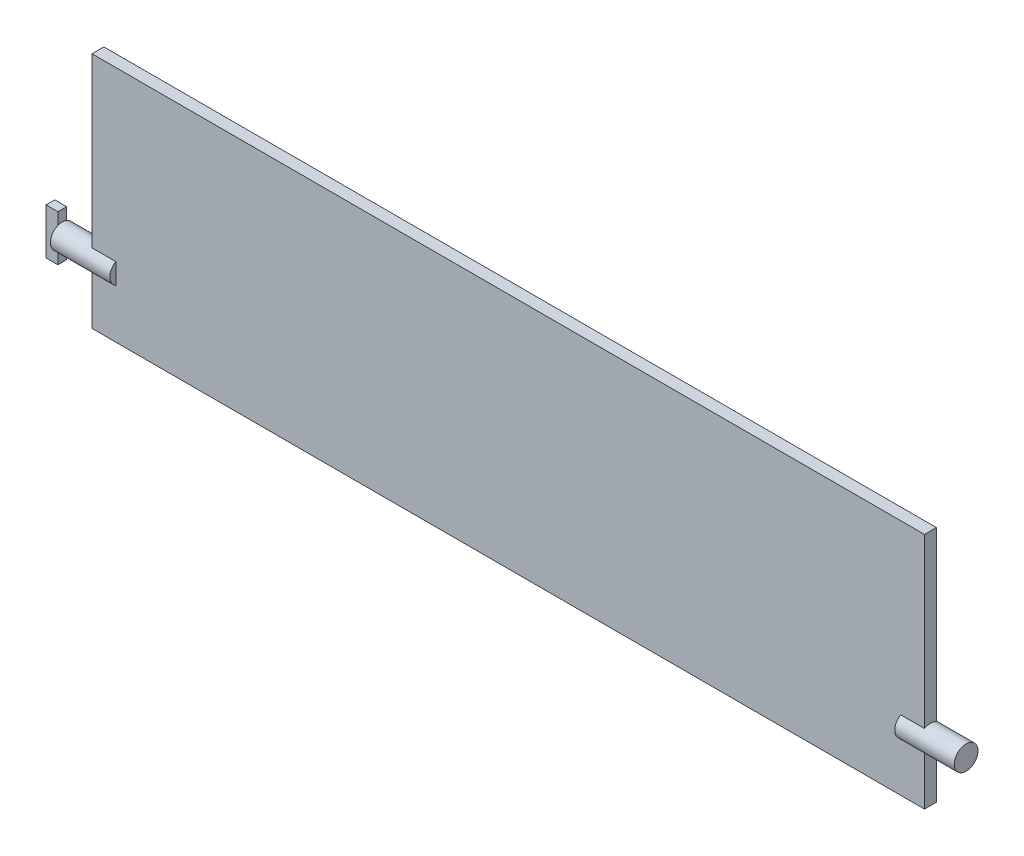
SolidWorks part; units mm, degrees
ref_plane "Front Plane" through (0, 0, 0) normal (0, 0, 1) x (1, 0, 0)
ref_plane "Top Plane" through (0, 0, 0) normal (0, 1, 0) x (1, 0, 0)
ref_plane "Right Plane" through (0, 0, 0) normal (1, 0, 0) x (0, 0, -1)
sketch "Sketch1" plane through (0, 0, 0) normal (0, 0, 1) x (1, 0, 0)
  line L1 (-175, -25) -> (175, -25)
  line L2 (-175, -25) -> (-175, 25)
  line L3 (-175, 25) -> (175, 25)
  line L4 (175, -25) -> (175, 25)
  line L5 (-175, -25) -> (175, 25) construction
  line L6 (-175, 25) -> (175, -25) construction
  point P0 (0, 0)
  dimension "D1" = 50
  dimension "D2" = 350
extrude "Boss-Extrude1" add sketch "Sketch1" along normal blind 5
sketch "Sketch2" plane through (-175, 0, 0) normal (-1, 0, 0) x (0, 0, 1)
  circle A0 centre (2.5, 0) radius 5
  dimension "D1" = 10
extrude "Boss-Extrude2" add sketch "Sketch2" along normal blind 15 and the other way blind 10
mirror "Mirror1" about plane through (0, 0, 0) normal (1, 0, 0) of "Boss-Extrude2"
sketch "Sketch4" plane through (0, 25, 0) normal (0, 1, 0) x (1, 0, 0)
  line L6 (-175, 0) -> (-175, -5)
  line L8 (-175, -5) -> (175, -5)
  line L9 (175, -5) -> (175, 0)
  line L11 (175, 0) -> (-175, 0)
  line L12 (-175, 0) -> (-175, -5)
  line L14 (-175, -5) -> (175, -5)
  line L15 (175, -5) -> (175, 0)
  line L17 (175, 0) -> (-175, 0)
  dimension "D1" = 0
extrude "Boss-Extrude4" add sketch "Sketch4" along normal blind 50
sketch "Sketch5" plane through (-190, 0, 0) normal (-1, 0, 0) x (0, 0, 1)
  line L1 (0.6656, 9.6559) -> (4.3344, 9.6559)
  line L2 (0.6656, 9.6559) -> (0.6656, -9.6559)
  line L3 (0.6656, -9.6559) -> (4.3344, -9.6559)
  line L4 (4.3344, 9.6559) -> (4.3344, -9.6559)
  line L5 (0.6656, 9.6559) -> (4.3344, -9.6559) construction
  line L6 (0.6656, -9.6559) -> (4.3344, 9.6559) construction
  point P0 (2.5, 0)
extrude "Boss-Extrude5" add sketch "Sketch5" along normal blind 5
